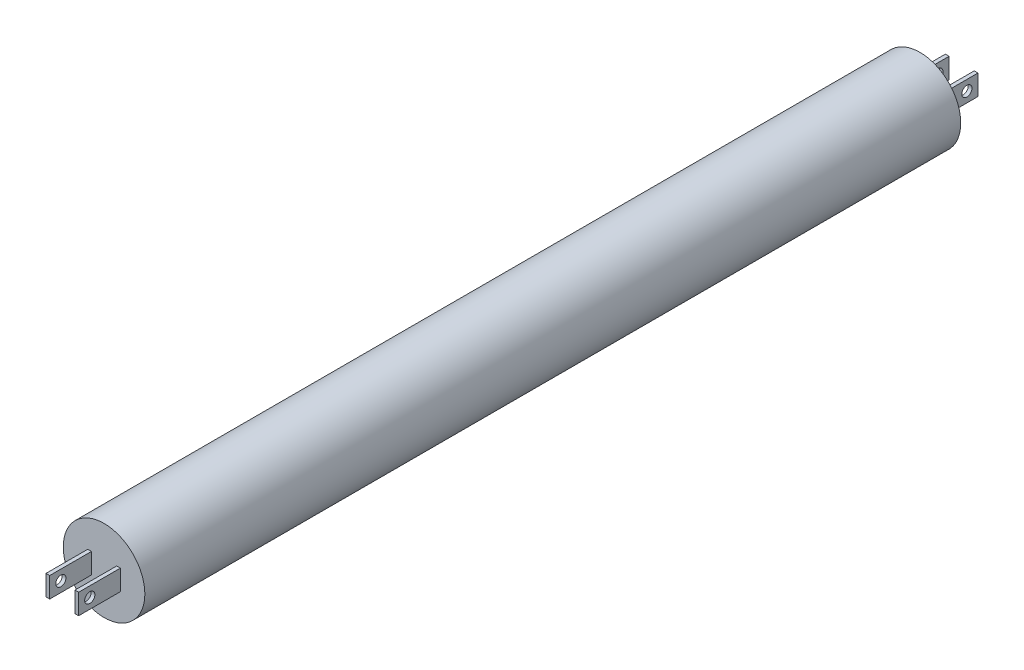
SolidWorks part; units mm, degrees
ref_plane "Front Plane" through (0, 0, 0) normal (0, 0, 1) x (1, 0, 0)
ref_plane "Top Plane" through (0, 0, 0) normal (0, 1, 0) x (1, 0, 0)
ref_plane "Right Plane" through (0, 0, 0) normal (1, 0, 0) x (0, 0, -1)
sketch "Sketch1" plane through (0, 0, 0) normal (0, 0, 1) x (1, 0, 0)
  circle A0 centre (0, 0) radius 20
extrude "Boss-Extrude1" add sketch "Sketch1" along normal mid plane 400
sketch "Sketch2" plane through (0, 0, 0) normal (0, 1, 0) x (1, 0, 0)
  line L0 (0, 0) -> (12.2549, 0)
  line L1 (0, 0) -> (0, 17.9996)
  line L2 (-20, -200) -> (20, -200) construction
  line L3 (-6.1805, -200) -> (-8, -200)
  line L4 (-6.1805, -200) -> (-6.1805, -220.46)
  line L5 (-6.1805, -220.46) -> (-8, -220.46)
  line L6 (-8, -200) -> (-8, -220.46)
  line L7 (6.1805, -220.46) -> (8, -220.46)
  line L8 (8, -200) -> (8, -220.46)
  line L9 (6.1805, -200) -> (8, -200)
  line L10 (6.1805, -200) -> (6.1805, -220.46)
  line L11 (6.1805, 200) -> (6.1805, 220.46)
  line L12 (6.1805, 200) -> (8, 200)
  line L13 (8, 200) -> (8, 220.46)
  line L14 (6.1805, 220.46) -> (8, 220.46)
  line L15 (-6.1805, 220.46) -> (-8, 220.46)
  line L16 (-8, 200) -> (-8, 220.46)
  line L17 (-6.1805, 200) -> (-8, 200)
  line L18 (-6.1805, 200) -> (-6.1805, 220.46)
  dimension "D1" = 12
  dimension "D2" = 20.46
extrude "Boss-Extrude2" add sketch "Sketch2" along normal mid plane 10 contours L9 L10 L7 L8 | L3 L6 L5 L4 | L14 L11 L12 L13 | L17 L18 L15 L16
sketch "Sketch3" plane through (0, 0, 0) normal (1, 0, 0) x (0, 0, -1)
  line L0 (0, 0) -> (0, 6.8961)
  circle A0 centre (-215, 0) radius 2.5
  circle A1 centre (215, 0) radius 2.5
extrude "Cut-Extrude1" cut sketch "Sketch3" against normal mid plane 18 contours A0 | A1
